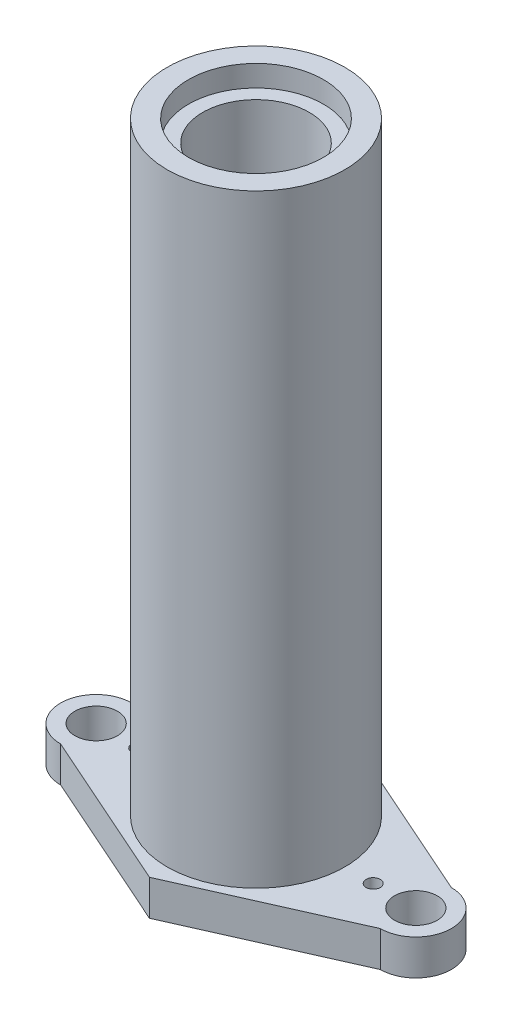
SolidWorks part; units mm, degrees
ref_plane "Спереди" through (0, 0, 0) normal (0, 0, 1) x (1, 0, 0)
ref_plane "Сверху" through (0, 0, 0) normal (0, 1, 0) x (1, 0, 0)
ref_plane "Справа" through (0, 0, 0) normal (1, 0, 0) x (0, 0, -1)
sketch "Эскиз1" plane through (0, 0, 0) normal (0, 1, 0) x (1, 0, 0)
  line L0 (-22.5, -0.8693) -> (0, -0.8693) construction
  line L1 (0, -0.8693) -> (22.5, -0.8693) construction
  line L2 (0, -0.8693) -> (0, 14.1307) construction
  line L3 (0, -0.8693) -> (0, -15.8693) construction
  line L4 (-22.5, -0.8693) -> (-22.5, 4.1307) construction
  line L5 (-22.5, -0.8693) -> (-22.5, -5.8693) construction
  line L6 (22.5, -0.8693) -> (22.5, 4.1307) construction
  line L7 (22.5, -0.8693) -> (22.5, -5.8693) construction
  line L8 (-22.5, 4.1307) -> (0, 14.1307)
  line L9 (0, 14.1307) -> (22.5, 4.1307)
  line L10 (22.5, -5.8693) -> (0, -15.8693)
  line L11 (0, -15.8693) -> (-22.5, -5.8693)
  line L12 (-22.5, -0.8693) -> (-16.5, -0.8693) construction
  line L13 (22.5, -0.8693) -> (16.5, -0.8693) construction
  circle A0 centre (-22.5, -0.8693) radius 3
  circle A1 centre (0, -0.8693) radius 10
  circle A2 centre (22.5, -0.8693) radius 3
  arc A3 (-22.5, 4.1307) -> (-22.5, -5.8693) centre (-22.5, -0.8693) ccw
  arc A4 (22.5, 4.1307) -> (22.5, -5.8693) centre (22.5, -0.8693) cw
  circle A5 centre (-16.5, -0.8693) radius 1
  circle A6 centre (16.5, -0.8693) radius 1
  dimension "D1" = 6
  dimension "D2" = 20
  dimension "D7" = 2
  dimension "D3" = 22.5
  dimension "D4" = 15
  dimension "D5" = 5
  dimension "D6" = 6
extrude "Бобышка-Вытянуть1" add sketch "Эскиз1" along normal blind 5 contours A4 L9 L8 A3 L11 L10 A2 A1 A0
sketch "Эскиз2" plane through (0, 5, 0) normal (0, 1, 0) x (1, 0, 0)
  circle A0 centre (0, -0.8693) radius 12.5
  circle A1 centre (0, -0.8693) radius 10
  dimension "D1" = 25
extrude "Бобышка-Вытянуть2" add sketch "Эскиз2" along normal blind 70
sketch "Эскиз3" plane through (0, 75, 0) normal (0, 1, 0) x (1, 0, 0)
  circle A0 centre (0, -0.8693) radius 12.5
extrude "Бобышка-Вытянуть3" add sketch "Эскиз3" along normal blind 15
sketch "Эскиз4" plane through (0, 90, 0) normal (0, 1, 0) x (1, 0, 0)
  circle A0 centre (0, -0.8693) radius 4
  dimension "D1" = 8
extrude "Вырез-Вытянуть1" cut sketch "Эскиз4" against normal through all
sketch "Эскиз5" plane through (0, 90, 0) normal (0, 1, 0) x (1, 0, 0)
  circle A0 centre (0, -0.8693) radius 7.5
  dimension "D1" = 15
extrude "Вырез-Вытянуть2" cut sketch "Эскиз5" against normal blind 12
sketch "Эскиз6" plane through (0, 90, 0) normal (0, 1, 0) x (1, 0, 0)
  circle A0 centre (0, -0.8693) radius 9.5
  dimension "D1" = 19
extrude "Вырез-Вытянуть3" cut sketch "Эскиз6" against normal blind 3
